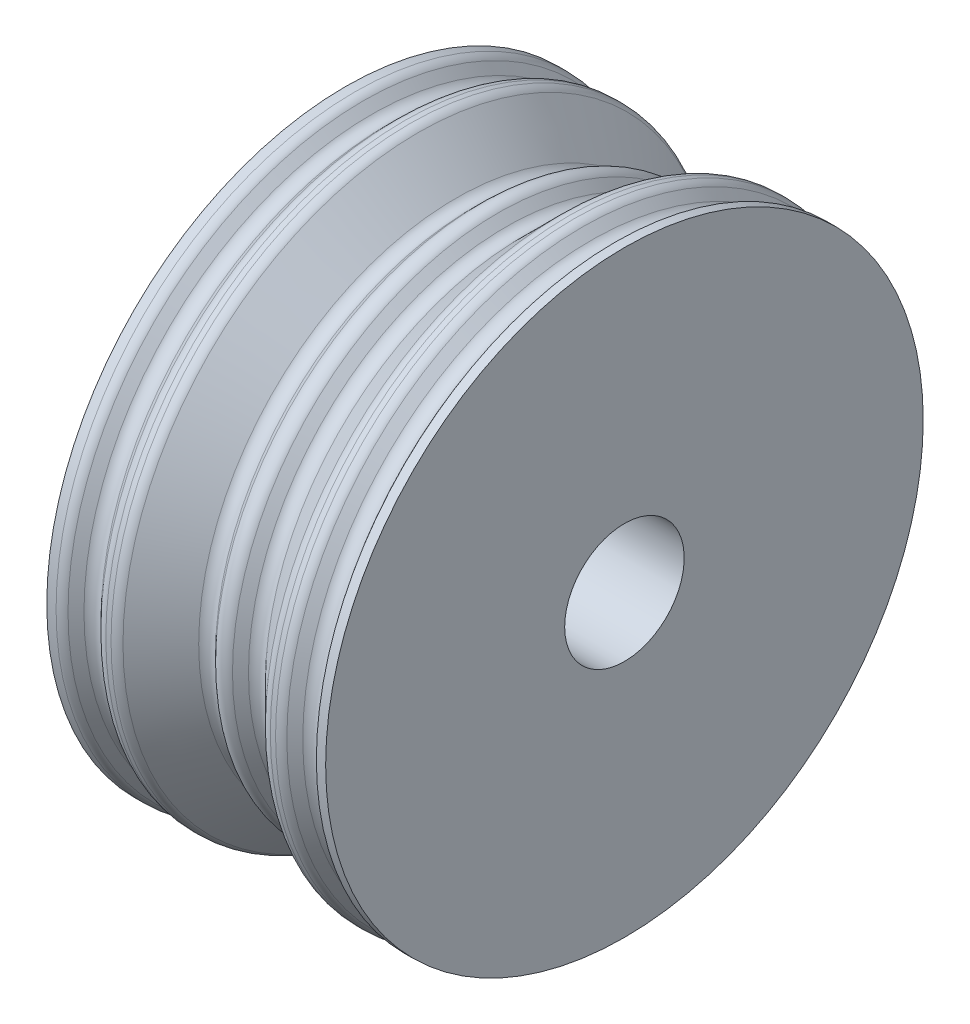
SolidWorks part; units mm, degrees
ref_plane "Front Plane" through (0, 0, 0) normal (0, 0, 1) x (1, 0, 0)
ref_plane "Top Plane" through (0, 0, 0) normal (0, 1, 0) x (1, 0, 0)
ref_plane "Right Plane" through (0, 0, 0) normal (1, 0, 0) x (0, 0, -1)
sketch "Sketch1" plane through (0, 0, 0) normal (0, 0, 1) x (1, 0, 0)
  line L0 (0, 3.81) -> (0, 19.05)
  line L1 (0, 19.05) -> (0.5926, 19.05)
  line L2 (1.1314, 18.8268) -> (1.6394, 18.3188)
  line L3 (2.7171, 18.3188) -> (3.2251, 18.8268)
  line L4 (3.7639, 19.05) -> (4.097, 19.05)
  line L5 (4.6358, 18.8268) -> (7.0488, 16.4138)
  line L6 (8.1264, 16.4138) -> (8.6363, 16.9237)
  line L7 (9.7139, 16.9237) -> (10.2238, 16.4138)
  line L8 (11.3014, 16.4138) -> (13.7144, 18.8268)
  line L9 (14.2532, 19.05) -> (14.5863, 19.05)
  line L10 (15.1035, 18.8477) -> (15.6311, 18.3601)
  line L11 (16.7634, 18.47) -> (17.1874, 19.05)
  line L12 (17.1874, 19.05) -> (17.78, 19.05)
  line L13 (17.78, 19.05) -> (17.78, 3.81)
  line L14 (17.78, 3.81) -> (0, 3.81)
  line L15 (0, 0) -> (9.7139, 0) construction
  arc A0 (13.7144, 18.8268) -> (14.2532, 19.05) centre (14.2532, 18.288) cw
  arc A1 (14.5863, 19.05) -> (15.1035, 18.8477) centre (14.5863, 18.288) cw
  arc A2 (0.5926, 19.05) -> (1.1314, 18.8268) centre (0.5926, 18.288) cw
  arc A3 (3.2251, 18.8268) -> (3.7639, 19.05) centre (3.7639, 18.288) cw
  arc A4 (4.097, 19.05) -> (4.6358, 18.8268) centre (4.097, 18.288) cw
  arc A5 (1.6394, 18.3188) -> (2.7171, 18.3188) centre (2.1782, 18.8576) ccw
  arc A6 (15.6311, 18.3601) -> (16.7634, 18.47) centre (16.1482, 18.9198) ccw
  arc A7 (10.2238, 16.4138) -> (11.3014, 16.4138) centre (10.7626, 16.9526) ccw
  arc A8 (7.0488, 16.4138) -> (8.1264, 16.4138) centre (7.5876, 16.9526) ccw
  arc A9 (8.6363, 16.9237) -> (9.7139, 16.9237) centre (9.1751, 16.3849) cw
  point P24 (3.4482, 19.05)
  point P29 (2.1782, 17.78)
  point P32 (16.2589, 17.78)
  point P35 (10.7626, 15.875)
  point P38 (7.5876, 15.875)
  dimension "D1" = 19.05
  dimension "D9" = 0.762
  dimension "D2" = 17.78
  dimension "D3" = 3.81
  dimension "D4" = 90
  dimension "D5" = 1.27
  dimension "D6" = 15.875
  dimension "D7" = 45
  dimension "D8" = 3.175
  dimension "D10" = 13.97
revolve "Revolve1" add sketch "Sketch1" angle 360 about L15
